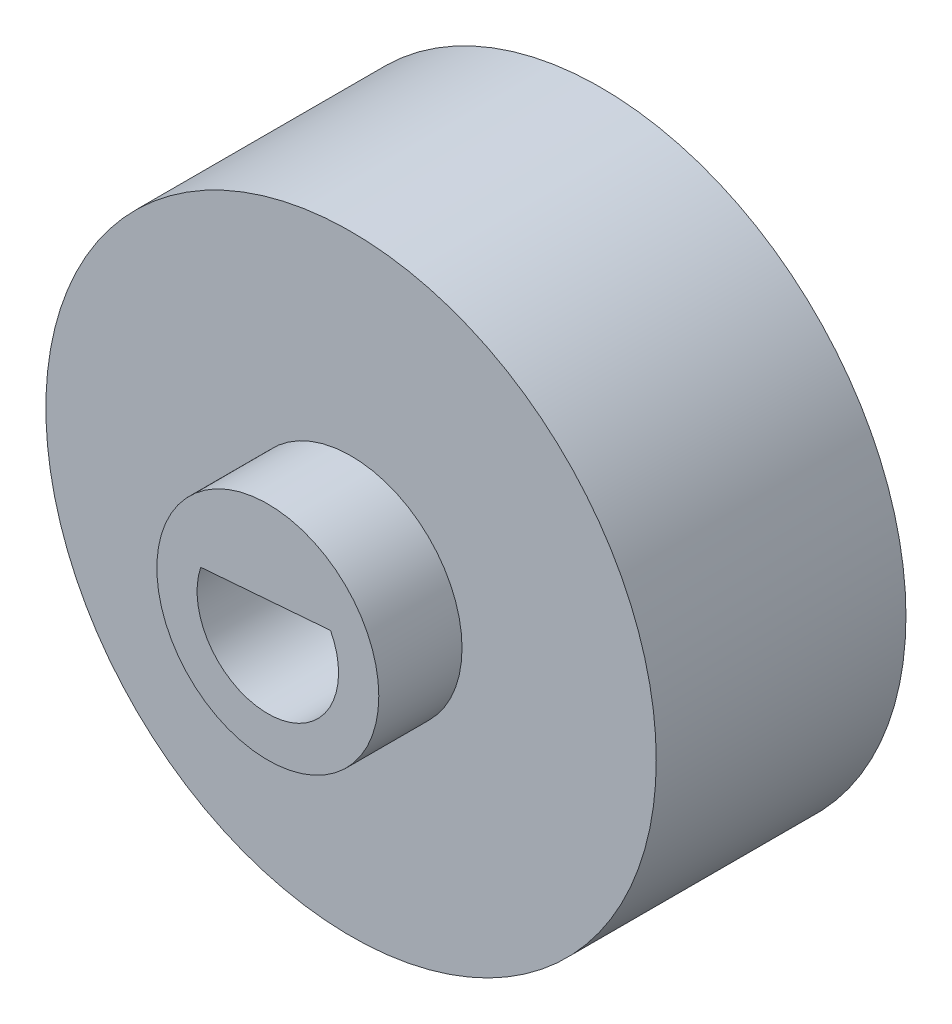
SolidWorks part; units mm, degrees
ref_plane "前视基准面" through (0, 0, 0) normal (0, 0, 1) x (1, 0, 0)
ref_plane "上视基准面" through (0, 0, 0) normal (0, 1, 0) x (1, 0, 0)
ref_plane "右视基准面" through (0, 0, 0) normal (1, 0, 0) x (0, 0, -1)
other "Configuration Table"
sketch "草图1" plane through (0, 0, 0) normal (0, 0, 1) x (1, 0, 0)
  line L0 (4.5201, 2.3619) -> (-4.8339, 1.6257)
  circle A0 centre (0, 0) radius 8
  arc A1 (-4.8339, 1.6257) -> (4.5201, 2.3619) centre (0, 0) ccw
extrude "凸台-拉伸1" add sketch "草图1" along normal blind 24
sketch "草图2" plane through (0, 0, 0) normal (0, 0, 1) x (1, 0, 0)
  circle A0 centre (0, 0) radius 22
  circle A1 centre (0, 0) radius 8
extrude "凸台-拉伸2" add sketch "草图2" along normal blind 18
sketch "草图3" plane through (0, 0, 0) normal (0, 0, 1) x (1, 0, 0)
  arc A0 (18.7119, -1.7536) -> (18.7119, 1.7536) centre (0, 0) ccw
  arc A1 (21.9756, 1.0349) -> (21.9756, -1.0349) centre (0, 0) cw
  spline S0 degree 4 poles (-2, -3) (-2.0022, -3.0033) (-2.0094, -3.014) (-2.024, -3.0355) (-2.0512, -3.0752) (-2.101, -3.147) (-2.1609, -3.2323) (-2.2188, -3.3138) (-2.2666, -3.3805) (-2.2906, -3.4139) (-2.3007, -3.4279) (-2.307, -3.4366) (-2.312, -3.4436) (-2.3171, -3.4507) (-2.3212, -3.4563) (-2.3243, -3.4608) (-2.3266, -3.4637) (-2.3277, -3.4658) (-2.3286, -3.468) (-2.3305, -3.4682) (-2.3318, -3.4703) (-2.333, -3.4732) (-2.335, -3.4753) (-2.3376, -3.4791) (-2.3408, -3.4834) (-2.3444, -3.4885) (-2.3486, -3.4942) (-2.3528, -3.5001) (-2.357, -3.5058) (-2.3602, -3.5102) (-2.3623, -3.5131) (-2.3633, -3.5145) knots 0 0 0 0 0 0.024872 0.082473 0.16476 0.305659 0.579946 0.744519 0.799377 0.826805 0.84052 0.854234 0.867949 0.881663 0.895377 0.898806 0.902235 0.905663 0.909092 0.911933 0.914774 0.920455 0.926137 0.931819 0.943182 0.954546 0.965909 0.977273 0.988636 1 1 1 1 1 construction
  spline S1 degree 4 poles (-2, -3) (-2.0022, -3.0033) (-2.0094, -3.014) (-2.024, -3.0355) (-2.0512, -3.0752) (-2.101, -3.147) (-2.1609, -3.2323) (-2.2188, -3.3138) (-2.2666, -3.3805) (-2.2906, -3.4139) (-2.3007, -3.4279) (-2.307, -3.4366) (-2.312, -3.4436) (-2.3171, -3.4507) (-2.3212, -3.4563) (-2.3243, -3.4608) (-2.3266, -3.4637) (-2.3277, -3.4658) (-2.3284, -3.4675) (-2.3293, -3.468) (-2.3297, -3.4682) knots 0 0 0 0 0 0.024872 0.082473 0.16476 0.305659 0.579946 0.744519 0.799377 0.826805 0.84052 0.854234 0.867949 0.881663 0.895377 0.898806 0.902235 0.905663 0.909092 0.909092 0.909092 0.909092 0.909092
  spline S2 degree 4 poles (-2.3525, -3.3828) (-2.3483, -3.3805) (-2.3458, -3.3748) (-2.3345, -3.3695) (-2.3295, -3.3614) (-2.3207, -3.3543) (-2.3107, -3.3449) (-2.2967, -3.3319) (-2.2793, -3.3152) (-2.2593, -3.2959) (-2.2397, -3.2765) (-2.2201, -3.2568) (-2.1912, -3.2271) (-2.1499, -3.1834) (-2.1051, -3.1335) (-2.062, -3.0821) (-2.0305, -3.0419) (-2.0137, -3.0194) (-2.0055, -3.0079) (-2.0013, -3.002) (-2, -3) knots 0 0 0 0 0 0.029059 0.058118 0.071394 0.084671 0.111224 0.16433 0.217436 0.270542 0.323649 0.376755 0.429861 0.589179 0.785071 0.891283 0.94439 0.981716 1 1 1 1 1 construction
  spline S3 degree 4 poles (-2.3297, -3.3625) (-2.3286, -3.3613) (-2.3264, -3.3589) (-2.3207, -3.3543) (-2.3107, -3.3449) (-2.2967, -3.3319) (-2.2793, -3.3152) (-2.2593, -3.2959) (-2.2397, -3.2765) (-2.2201, -3.2568) (-2.1912, -3.2271) (-2.1499, -3.1834) (-2.1051, -3.1335) (-2.062, -3.0821) (-2.0305, -3.0419) (-2.0137, -3.0194) (-2.0055, -3.0079) (-2.0013, -3.002) (-2, -3) knots 0.058118 0.058118 0.058118 0.058118 0.058118 0.071394 0.084671 0.111224 0.16433 0.217436 0.270542 0.323649 0.376755 0.429861 0.589179 0.785071 0.891283 0.94439 0.981716 1 1 1 1 1
